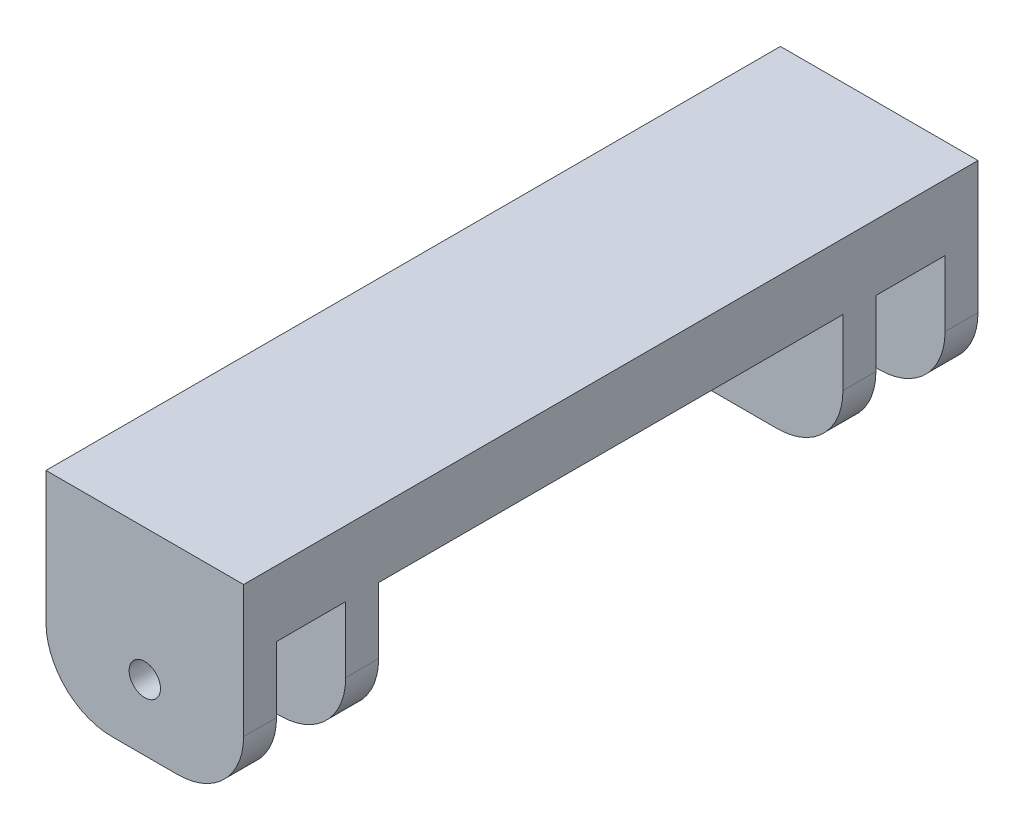
SolidWorks part; units mm, degrees
ref_plane "Plan de face" through (0, 0, 0) normal (0, 0, 1) x (1, 0, 0)
ref_plane "Plan de dessus" through (0, 0, 0) normal (0, 1, 0) x (1, 0, 0)
ref_plane "Plan de droite" through (0, 0, 0) normal (1, 0, 0) x (0, 0, -1)
sketch "Esquisse1" plane through (0, 0, 0) normal (0, 0, 1) x (1, 0, 0)
  line L1 (0, 0) -> (30, 0)
  line L2 (0, 0) -> (0, 10)
  line L3 (0, 10) -> (30, 10)
  line L4 (30, 0) -> (30, 10)
  dimension "D1" = 30
  dimension "D2" = 10
extrude "Boss.-Extru.1" add sketch "Esquisse1" along normal blind 111.5
sketch "Esquisse2" plane through (0, 0, 0) normal (0, -1, 0) x (1, 0, 0)
  line L0 (30, 111.5) -> (30, 0) construction
  line L1 (0, 0) -> (30, 0)
  line L2 (0, 0) -> (0, 5)
  line L3 (0, 5) -> (30, 5)
  line L4 (30, 0) -> (30, 5)
  line L5 (0, 111.5) -> (0, 0) construction
  line L6 (30, 15.5) -> (0, 15.5)
  line L7 (30, 15.5) -> (30, 20.5)
  line L8 (30, 20.5) -> (0, 20.5)
  line L9 (0, 15.5) -> (0, 20.5)
  line L11 (0, 111.5) -> (30, 111.5)
  line L12 (0, 111.5) -> (0, 106.5)
  line L13 (0, 106.5) -> (30, 106.5)
  line L14 (30, 111.5) -> (30, 106.5)
  line L15 (30, 96) -> (0, 96)
  line L16 (30, 96) -> (30, 91)
  line L17 (30, 91) -> (0, 91)
  line L18 (0, 96) -> (0, 91)
  dimension "D1" = 5
  dimension "D2" = 5
  dimension "D3" = 5
  dimension "D4" = 5
  dimension "D5" = 10.5
  dimension "D6" = 10.5
extrude "Boss.-Extru.2" add sketch "Esquisse2" along normal blind 20
hole_wizard "Perçage pour écrous auto-bloquants 300® #6 (SP)1" positions "Esquisse3" profile "Esquisse4" hole size "#6-32" standard "PEM® Inch" end condition through all
sketch "Esquisse3" plane through (0, 0, 111.5) normal (0, 0, 1) x (1, 0, 0)
  line L0 (0, -10) -> (15, -10) construction
  line L1 (0, 10) -> (0, -20) construction
  line L2 (15, -10) -> (30, -10) construction
  line L3 (30, -20) -> (30, 10) construction
  line L5 (30, -20) -> (0, -20) construction
  point P0 (15, -10)
  dimension "D1" = 10
sketch "Esquisse4" plane through (15, -10, 111.5) normal (1, 0, 0) x (0, -1, 0)
  line L0 (0, 0) -> (0, 111.5)
  line L1 (0, 111.5) -> (2.3812, 111.5)
  line L2 (2.3812, 111.5) -> (2.3812, 0)
  line L5 (2.3812, 0) -> (0, 0)
  line L11 (0, -6.35) -> (0, 107.95) construction
  dimension "Diamètre du perçage jusqu'au prochain" = 4.7625
  dimension "Profondeur du perçage jusqu'au prochain" = 111.5
fillet "Congé1" radius 10 8 edges at (0, -20, 2.5) (30, -20, 2.5) (30, -20, 93.5) (30, -20, 109) (0, -20, 93.5) (0, -20, 109) (0, -20, 18) (30, -20, 18)
